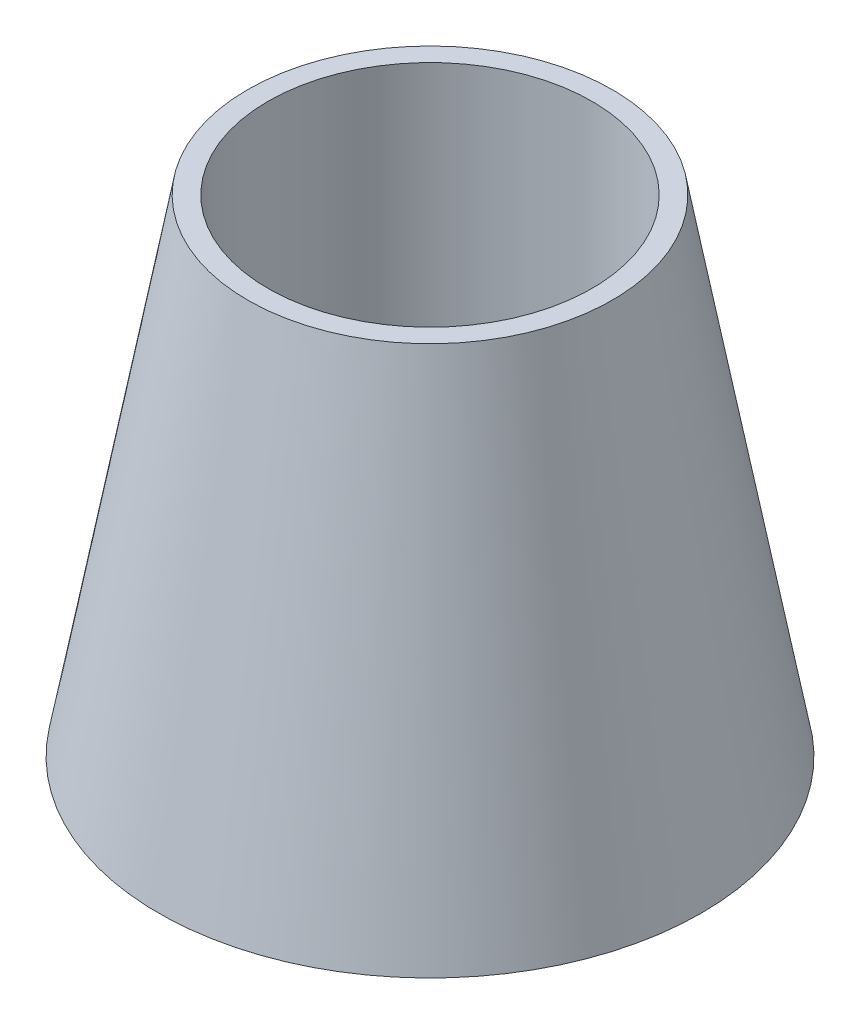
SolidWorks part; units mm, degrees
ref_plane "Front Plane" through (0, 0, 0) normal (0, 0, 1) x (1, 0, 0)
ref_plane "Top Plane" through (0, 0, 0) normal (0, 1, 0) x (1, 0, 0)
ref_plane "Right Plane" through (0, 0, 0) normal (1, 0, 0) x (0, 0, -1)
sketch "Sketch1" plane through (0, 0, 0) normal (0, 0, 1) x (1, 0, 0)
  line L0 (0, 0) -> (-78.74, 0)
  line L1 (-78.74, 0) -> (-77.5758, 6.35) construction
  line L2 (-50.8, 152.4) -> (0, 152.4) construction
  line L3 (0, 152.4) -> (0, 0) construction
  line L4 (-78.74, 0) -> (-85.09, 0)
  line L5 (-85.09, 0) -> (-57.15, 152.4)
  line L6 (-57.15, 152.4) -> (-50.8, 152.4)
  line L7 (-50.8, 152.4) -> (-50.8, 8.89)
  line L9 (-57.15, 8.89) -> (-57.15, 117.7636)
  line L10 (-57.15, 117.7636) -> (-57.15, 152.4) construction
  line L11 (-57.15, 117.7636) -> (-50.8, 152.4) construction
  line L12 (-59.69, 6.35) -> (-74.5278, 6.35)
  line L13 (-77.0262, 9.348) -> (-57.15, 117.7636)
  line L14 (0, 0) -> (0, 6.35)
  line L15 (0, 6.35) -> (-48.26, 6.35)
  arc A0 (-50.8, 8.89) -> (-48.26, 6.35) centre (-48.26, 8.89) ccw
  arc A1 (-59.69, 6.35) -> (-57.15, 8.89) centre (-59.69, 8.89) ccw
  arc A2 (-77.0262, 9.348) -> (-74.5278, 6.35) centre (-74.5278, 8.89) ccw
  dimension "D6" = 2.54
  dimension "D1" = 6.35
  dimension "D2" = 85.09
  dimension "D3" = 152.4
  dimension "D4" = 57.15
  dimension "D5" = 6.35
revolve "Revolve1" add sketch "Sketch1" angle 360 about L3
sketch "Sketch2" plane through (0, 6.35, 0) normal (0, 1, 0) x (1, 0, 0)
  line L0 (0, 0) -> (0, 7.328) construction
  circle A0 centre (0, 0) radius 3.175
  circle A1 centre (25.4, 0) radius 3.175
  circle A2 centre (-25.4, 0) radius 3.175
  dimension "D1" = 6.35
  dimension "D2" = 6.35
  dimension "D3" = 25.4
extrude "Cut-Extrude1" cut sketch "Sketch2" against normal up to next
